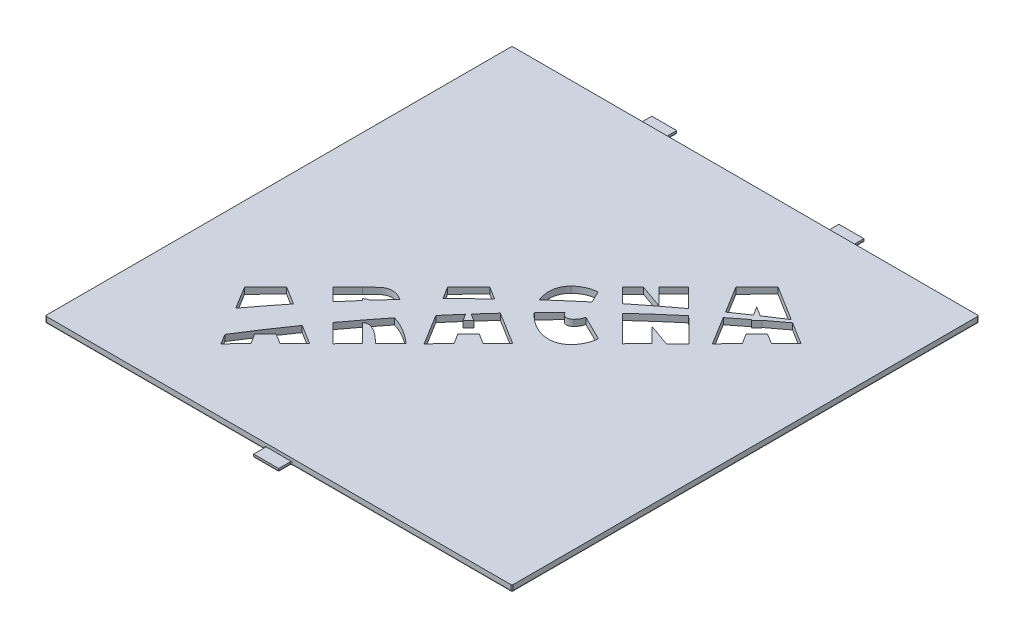
SolidWorks part; units mm, degrees
ref_plane "Front Plane" through (0, 0, 0) normal (0, 0, 1) x (1, 0, 0)
ref_plane "Top Plane" through (0, 0, 0) normal (0, 1, 0) x (1, 0, 0)
ref_plane "Right Plane" through (0, 0, 0) normal (1, 0, 0) x (0, 0, -1)
sketch "Sketch1" plane through (0, 0, 0) normal (0, 1, 0) x (1, 0, 0)
  line L1 (-37.4, 37.4) -> (37.4, 37.4)
  line L2 (-37.4, 37.4) -> (-37.4, -37.4)
  line L3 (-37.4, -37.4) -> (37.4, -37.4)
  line L4 (37.4, 37.4) -> (37.4, -37.4)
  line L5 (-37.4, 37.4) -> (37.4, -37.4) construction
  line L6 (-37.4, -37.4) -> (37.4, 37.4) construction
  point P0 (0, 0)
  dimension "D1" = 74.8
extrude "Boss-Extrude1" add sketch "Sketch1" along normal blind 1
sketch "Sketch3" plane through (0, 0, 0) normal (0, 1, 0) x (1, 0, 0)
  line L0 (-37.4, -37.4) -> (37.4, -37.4) construction
  line L1 (-2, -39.4) -> (2, -39.4)
  line L2 (-2, -39.4) -> (-2, -37.4)
  line L3 (-2, -37.4) -> (2, -37.4)
  line L4 (2, -39.4) -> (2, -37.4)
  line L5 (-2, -39.4) -> (2, -37.4) construction
  line L6 (-2, -37.4) -> (2, -39.4) construction
  line L7 (37.4, 37.4) -> (-37.4, 37.4) construction
  line L8 (-17, 39.4) -> (-13, 39.4)
  line L9 (-17, 39.4) -> (-17, 37.4)
  line L10 (-17, 37.4) -> (-13, 37.4)
  line L11 (-13, 39.4) -> (-13, 37.4)
  line L12 (-17, 39.4) -> (-13, 37.4) construction
  line L13 (-17, 37.4) -> (-13, 39.4) construction
  line L14 (0, -0.4875) -> (0, -13.2444) construction
  line L15 (13, 39.4) -> (17, 39.4)
  line L16 (13, 39.4) -> (13, 37.4)
  line L17 (13, 37.4) -> (17, 37.4)
  line L18 (17, 39.4) -> (17, 37.4)
  line L19 (13, 39.4) -> (17, 37.4) construction
  line L20 (13, 37.4) -> (17, 39.4) construction
  point P0 (0, -38.4)
  point P7 (-15, 38.4)
  point P14 (15, 38.4)
  dimension "D1" = 2
  dimension "D2" = 4
  dimension "D3" = 30
extrude "Boss-Extrude2" add sketch "Sketch3" along normal blind 0.5
fillet "Fillet1" radius 0.2 26 edges at (17, 0, -38.4) (15, 0, -39.4) (13, 0, -38.4) (-15, 0, -39.4) (-37.4, 0, 0) (0, 0, 39.4) (37.4, 0, 0) (13, 0.25, -37.4) (17, 0.25, -37.4) (-37.4, 0.5, -37.4) (-37.4, 0.5, 37.4) (37.4, 0.5, 37.4) (37.4, 0.5, -37.4)
sketch "Sketch4" plane through (0, 0, 0) normal (0, 1, 0) x (1, 0, 0)
  line L0 (-23.72, -31.4982) -> (31.2982, 23.52) construction
  line L1 (-37.2, -37.4) -> (37.2, -37.4) construction
  line L2 (-37.4, 37.2) -> (37.2, -37.4) construction
  text T0 "ARACNA" font "Gill Sans Ultra Bold Condensed" height 11
  point P7 (3.7891, -3.9891)
  dimension "D1" = 45
  dimension "D2" = 5.5
extrude "Cut-Extrude2" cut sketch "Sketch4" along normal through all
sketch "Sketch5" plane through (0, 0, 0) normal (0, 1, 0) x (1, 0, 0)
  line L0 (-24.4694, -22.8266) -> (-24.4694, -32.3637)
  spline S0 degree 2 poles (-24.4694, -22.8266) (-2.2482, 7.7281) (30.707, 26.5615) knots 0 0 0 1 1 1
  spline S1 degree 2 poles (30.707, 26.5615) (-4.1255, 3.4431) (-24.4694, -32.3637) knots 0 0 0 1 1 1
extrude "Boss-Extrude3" add sketch "Sketch5" along normal blind 1
